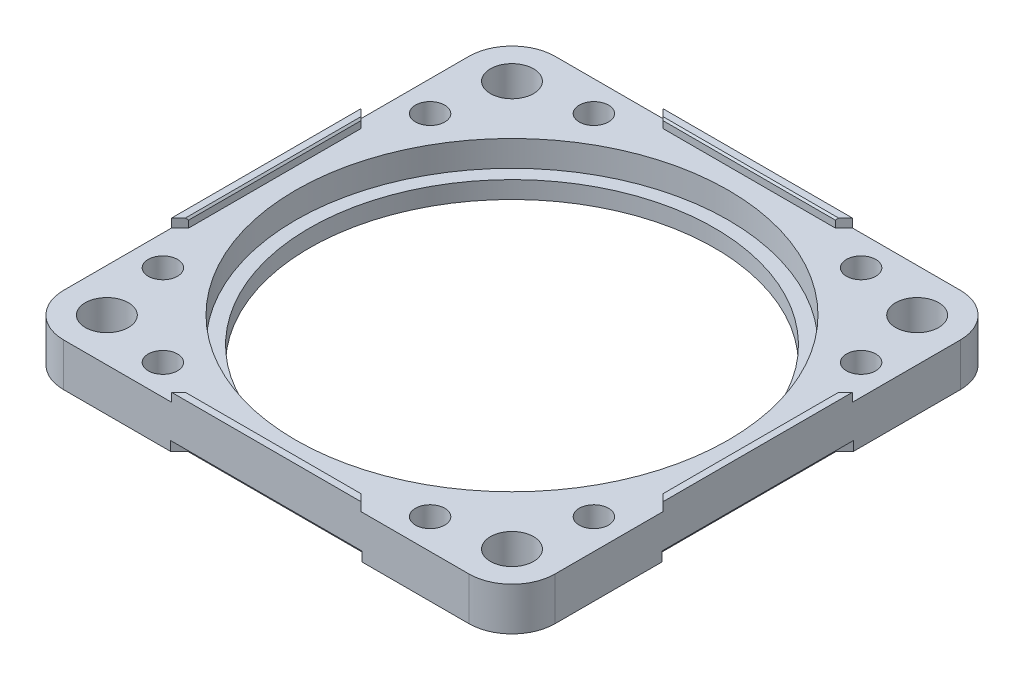
SolidWorks part; units mm, degrees
ref_plane "前视基准面" through (0, 0, 0) normal (0, 0, 1) x (1, 0, 0)
ref_plane "上视基准面" through (0, 0, 0) normal (0, 1, 0) x (1, 0, 0)
ref_plane "右视基准面" through (0, 0, 0) normal (1, 0, 0) x (0, 0, -1)
sketch "草图1" plane through (0, 0, 0) normal (0, 1, 0) x (1, 0, 0)
  line L1 (-28.5, -28.5) -> (28.5, -28.5)
  line L2 (-28.5, -28.5) -> (-28.5, 28.5)
  line L3 (-28.5, 28.5) -> (28.5, 28.5)
  line L4 (28.5, -28.5) -> (28.5, 28.5)
  line L5 (-28.5, -28.5) -> (28.5, 28.5) construction
  line L6 (-28.5, 28.5) -> (28.5, -28.5) construction
  point P0 (0, 0)
  dimension "D1" = 57
extrude "凸台-拉伸1" add sketch "草图1" along normal blind 5
sketch "草图2" plane through (0, 5, 0) normal (0, 1, 0) x (1, 0, 0)
  circle A0 centre (0, 0) radius 25.1
  dimension "D1" = 50.2
extrude "切除-拉伸1" cut sketch "草图2" against normal blind 3
sketch "草图8" plane through (0, 2, 0) normal (0, 1, 0) x (1, 0, 0)
  circle A0 centre (0, 0) radius 23.5
  dimension "D1" = 47
extrude "切除-拉伸5" cut sketch "草图8" against normal through all and the other way through all
sketch "草图3" plane through (0, 5, 0) normal (0, 1, 0) x (1, 0, 0)
  line L0 (0, 0) -> (23.5, 23.5) construction
  line L1 (0, 0) -> (0, -50000) construction
  line L2 (28.5, -28.5) -> (28.5, 28.5) construction
  circle A0 centre (23.5, 23.5) radius 2.5
  circle A1 centre (25, 15.5) radius 1.7
  circle A2 centre (15.5, 25) radius 1.7
  dimension "D1" = 5
  dimension "D6" = 3.4
  dimension "D2" = 45
  dimension "D3" = 47
  dimension "D4" = 8
  dimension "D5" = 3.5
extrude "切除-拉伸2" cut sketch "草图3" against normal through all
sketch "草图7" plane through (0, 0, 0) normal (0, -1, 0) x (1, 0, 0)
  line L1 (27.75, -13.9123) -> (25, -12.3246)
  line L2 (25, -12.3246) -> (22.25, -13.9123)
  line L3 (22.25, -13.9123) -> (22.25, -17.0877)
  line L4 (22.25, -17.0877) -> (25, -18.6754)
  line L5 (25, -18.6754) -> (27.75, -17.0877)
  line L6 (27.75, -17.0877) -> (27.75, -13.9123)
  circle A0 centre (25, -15.5) radius 2.75 construction
  dimension "D1" = 5.5
extrude "切除-拉伸4" cut sketch "草图7" against normal blind 2.5
sketch "草图4" plane through (0, 5, 0) normal (0, 1, 0) x (1, 0, 0)
  line L0 (28.5, 11) -> (27.5, 10)
  line L1 (28.5, -28.5) -> (28.5, 28.5) construction
  line L2 (27.5, 10) -> (27.5, -10)
  line L3 (27.5, -10) -> (28.5, -11)
  line L4 (28.5, -11) -> (28.5, 11)
  line L5 (0, 0) -> (27.5, 0) construction
  dimension "D1" = 135
  dimension "D2" = 135
  dimension "D3" = 1
  dimension "D4" = 22
extrude "凸台-拉伸2" add sketch "草图4" along normal blind 1
chamfer "倒角1" distance 0.2 angle 45 1 edges at (27.5, 6, 0)
sketch "草图5" plane through (0, 0, 0) normal (0, -1, 0) x (1, 0, 0)
  line L0 (28.5, 11.1) -> (27.5, 10.1)
  line L1 (28.5, 28.5) -> (28.5, -28.5) construction
  line L2 (27.5, 10.1) -> (27.5, -10.1)
  line L3 (27.5, -10.1) -> (28.5, -11.1)
  line L4 (28.5, -11.1) -> (28.5, 11.1)
  line L5 (0, 0) -> (27.5, 0) construction
  dimension "D1" = 22.2
  dimension "D2" = 135
  dimension "D3" = 135
  dimension "D4" = 1
extrude "切除-拉伸3" cut sketch "草图5" against normal blind 1.1
pattern_circular "阵列(圆周)1" count 4 over 360 about axis through (0, 0, 0) along (0, 1, 0) of "切除-拉伸2", "凸台-拉伸2", "倒角1", "切除-拉伸3", "切除-拉伸4"
fillet "圆角1" radius 5 4 edges at (-28.5, 2.5, -28.5) (-28.5, 2.5, 28.5) (28.5, 2.5, -28.5) (28.5, 2.5, 28.5)
